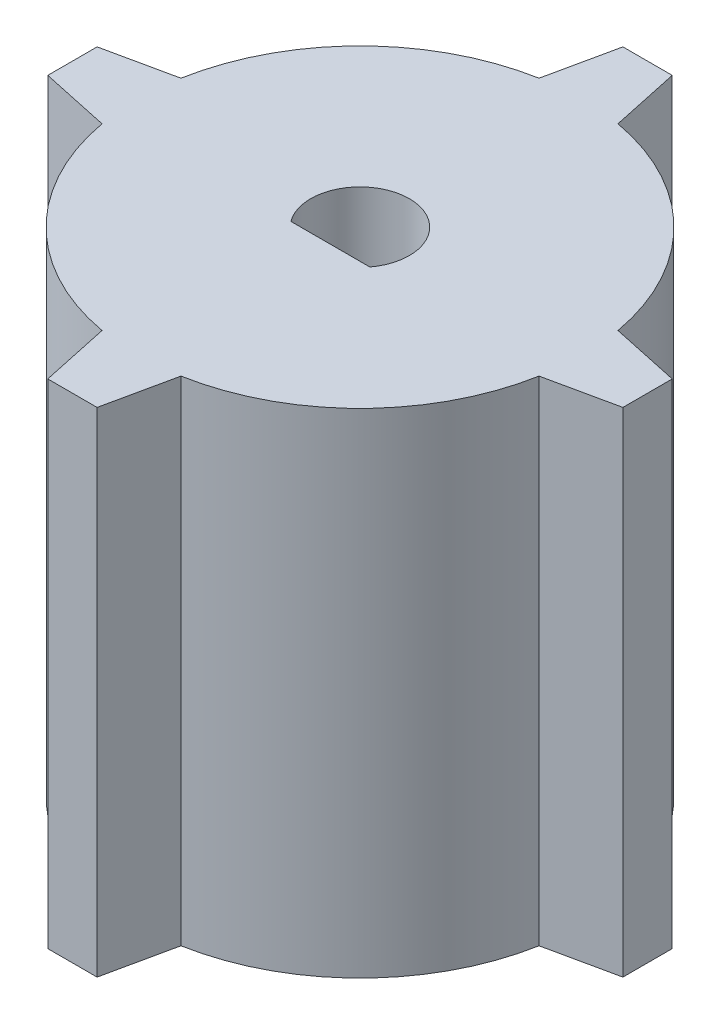
SolidWorks part; units mm, degrees
ref_plane "Front Plane" through (0, 0, 0) normal (0, 0, 1) x (1, 0, 0)
ref_plane "Top Plane" through (0, 0, 0) normal (0, 1, 0) x (1, 0, 0)
ref_plane "Right Plane" through (0, 0, 0) normal (1, 0, 0) x (0, 0, -1)
sketch "Sketch1" plane through (0, 0, 0) normal (0, 1, 0) x (1, 0, 0)
  line L0 (-2.032, -1.524) -> (2.032, -1.524)
  line L1 (-2.032, 11.2479) -> (-1.27, 14.8039)
  line L2 (-1.27, 14.8039) -> (1.27, 14.8039)
  line L3 (1.27, 14.8039) -> (2.032, 11.2479)
  line L4 (14.8039, -1.27) -> (11.2479, -2.032)
  line L5 (14.8039, 1.27) -> (14.8039, -1.27)
  line L6 (11.2479, 2.032) -> (14.8039, 1.27)
  line L7 (-1.27, -14.8039) -> (-2.032, -11.2479)
  line L8 (1.27, -14.8039) -> (-1.27, -14.8039)
  line L9 (2.032, -11.2479) -> (1.27, -14.8039)
  line L10 (-14.8039, 1.27) -> (-11.2479, 2.032)
  line L11 (-14.8039, -1.27) -> (-14.8039, 1.27)
  line L12 (-11.2479, -2.032) -> (-14.8039, -1.27)
  arc A0 (-11.2479, -2.032) -> (-2.032, -11.2479) centre (0, 0) ccw
  arc A1 (-2.032, -1.524) -> (2.032, -1.524) centre (0, 0) cw
  arc A2 (-2.032, 11.2479) -> (-11.2479, 2.032) centre (0, 0) ccw
  arc A3 (11.2479, 2.032) -> (2.032, 11.2479) centre (0, 0) ccw
  arc A4 (2.032, -11.2479) -> (11.2479, -2.032) centre (0, 0) ccw
  point P6 (0, 2.54)
  point P11 (0, 14.8039)
  point P14 (0, 0)
  point P26 (0, 0)
  dimension "D1" = 22.86
  dimension "D2" = 2.54
  dimension "D3" = 4.064
  dimension "D4" = 2.54
  dimension "D5" = 3.556
  dimension "D6" = 4
extrude "Boss-Extrude1" add sketch "Sketch1" along normal blind 25.4
